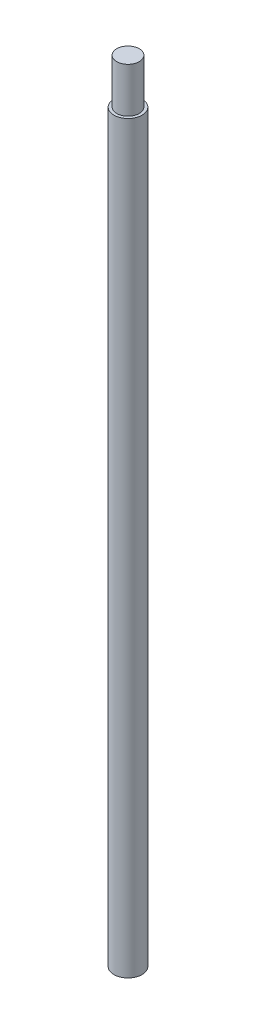
SolidWorks part; units mm, degrees
ref_plane "정면" through (0, 0, 0) normal (0, 0, 1) x (1, 0, 0)
ref_plane "윗면" through (0, 0, 0) normal (0, 1, 0) x (1, 0, 0)
ref_plane "우측면" through (0, 0, 0) normal (1, 0, 0) x (0, 0, -1)
sketch "스케치1" plane through (0, 0, 0) normal (0, 1, 0) x (1, 0, 0)
  circle A0 centre (0, 0) radius 5
  dimension "D1" = 10
extrude "보스-돌출1" add sketch "스케치1" along normal blind 281
sketch "스케치2" plane through (0, 281, 0) normal (0, 1, 0) x (1, 0, 0)
  circle A0 centre (0, 0) radius 4
  circle A1 centre (0, 0) radius 16
extrude "컷-돌출1" cut sketch "스케치2" against normal blind 16
